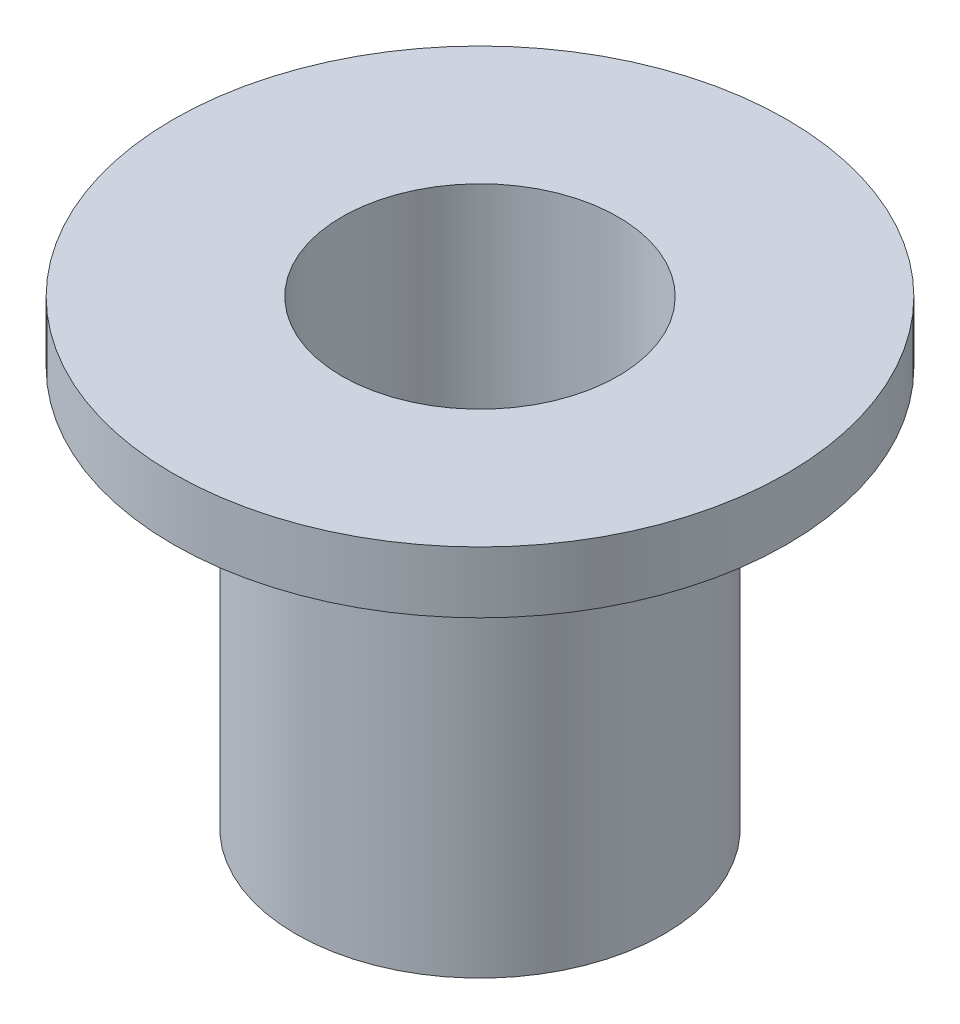
SolidWorks part; units mm, degrees
ref_plane "Plan de face" through (0, 0, 0) normal (0, 0, 1) x (1, 0, 0)
ref_plane "Plan de dessus" through (0, 0, 0) normal (0, 1, 0) x (1, 0, 0)
ref_plane "Plan de droite" through (0, 0, 0) normal (1, 0, 0) x (0, 0, -1)
sketch "Esquisse1" plane through (0, 0, 0) normal (0, 1, 0) x (1, 0, 0)
  circle A0 centre (0, 0) radius 6
  dimension "D1" = 12
extrude "Boss.-Extru.1" add sketch "Esquisse1" along normal blind 15
sketch "Esquisse2" plane through (0, 15, 0) normal (0, 1, 0) x (1, 0, 0)
  circle A0 centre (0, 0) radius 4.5
  dimension "D1" = 9
sketch "Esquisse3" plane through (0, 15, 0) normal (0, 1, 0) x (1, 0, 0)
  circle A0 centre (0, 0) radius 10
  dimension "D1" = 20
extrude "Boss.-Extru.2" add sketch "Esquisse3" against normal blind 2
extrude "Enlèv. mat.-Extru.2" cut sketch "Esquisse2" against normal blind 13
sketch "Esquisse4" plane through (0, 2, 0) normal (0, 1, 0) x (1, 0, 0)
  circle A0 centre (0, 0) radius 1.25
  dimension "D1" = 2.5
extrude "Enlèv. mat.-Extru.3" cut sketch "Esquisse4" against normal through all
